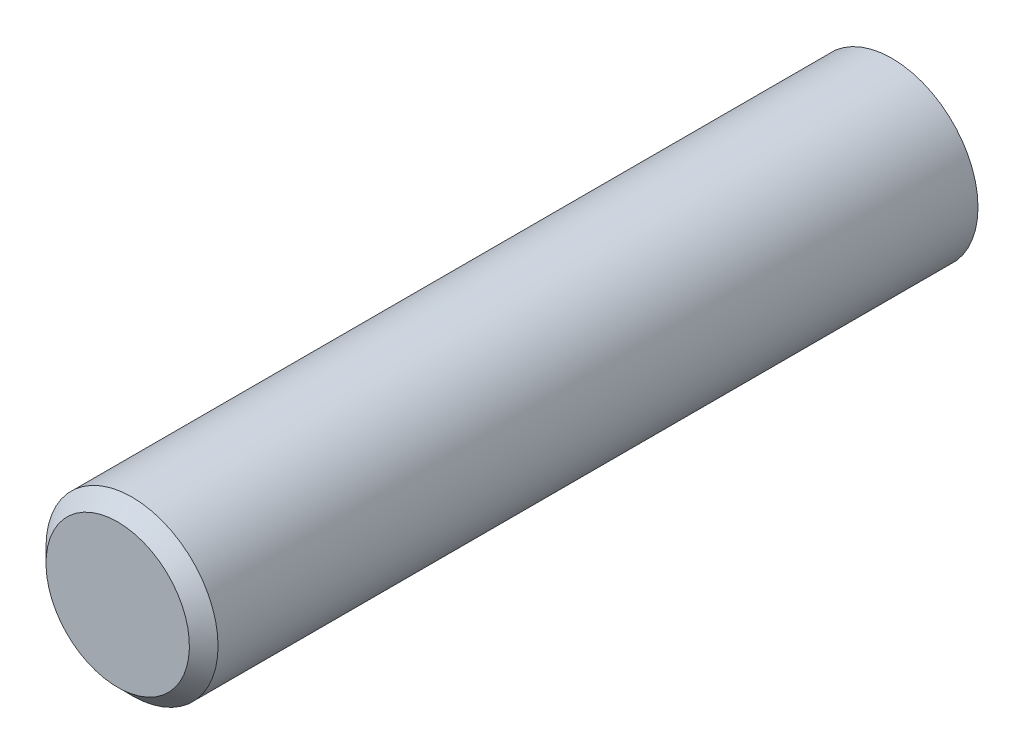
SolidWorks part; units mm, degrees
ref_plane "Ebene vorne" through (0, 0, 0) normal (0, 0, 1) x (1, 0, 0)
ref_plane "Ebene oben" through (0, 0, 0) normal (0, 1, 0) x (1, 0, 0)
ref_plane "Ebene rechts" through (0, 0, 0) normal (1, 0, 0) x (0, 0, -1)
ref_plane "Ebene1" through (78.75, 0, 0) normal (1, 0, 0) x (0, 0, -1)
sketch "Skizze1" plane through (78.75, 0, 0) normal (1, 0, 0) x (0, 0, -1)
  line L1 (-2, 3) -> (-2, 0) construction
  line L2 (2, 3) -> (-22, 3) construction
  line L3 (-22, 0) -> (0, 0) construction
  line L5 (-2, 3) -> (-2, 0)
  line L6 (-2, 3) -> (-22, 3)
  line L7 (-22, 0) -> (-2, 0)
  line L8 (-29, 0) -> (-22, 0) construction
  line L9 (-29, 3) -> (-29, 0) construction
  line L10 (-22, 3) -> (-29, 3) construction
  line L11 (-29, 0) -> (-22, 0)
  line L12 (-29, 3) -> (-29, 0)
  line L13 (-22, 3) -> (-29, 3)
revolve "Rotation1" add sketch "Skizze1" angle 360 about L7
sketch "Skizze4" plane through (0, 0, 2) normal (0, 0, -1) x (-1, 0, 0)
  point P0 (-78.75, 0)
hole_wizard "Ø3.1 (3.175) Durchmesser Bohrung1" positions "Skizze4" profile "Skizze5" hole size "Ø3.1" standard "DIN"
sketch "Skizze5" plane through (78.75, 0, 2) normal (1, 0, 0) x (0, 1, 0)
  line L0 (0, 0) -> (0, 10.9539)
  line L1 (0, 10.9539) -> (1.5875, 10)
  line L2 (1.5875, 10) -> (1.5875, 0)
  line L5 (1.5875, 0) -> (0, 0)
  line L10 (0, 10.9539) -> (-1.5875, 10) construction
  line L11 (0, -6.35) -> (0, 107.95) construction
  dimension "Bohrerdurchmesser" = 3.175
  dimension "Bohrungstiefe" = 10
  dimension "Spitzenwinkel" = 118
chamfer "Fase1" distance 0.5 angle 45 1 edges at (78.75, -3, 29)
